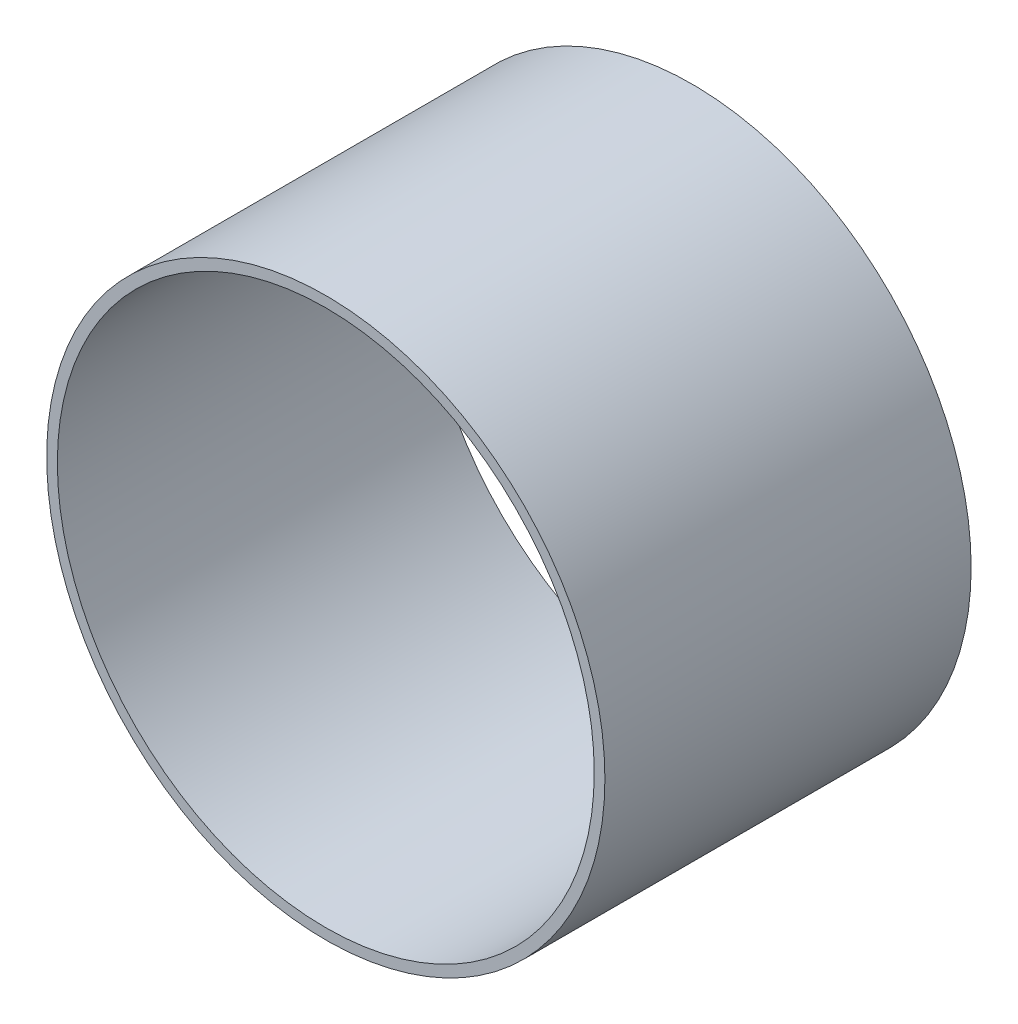
SolidWorks part; units mm, degrees
ref_plane "Спереди" through (0, 0, 0) normal (0, 0, 1) x (1, 0, 0)
ref_plane "Сверху" through (0, 0, 0) normal (0, 1, 0) x (1, 0, 0)
ref_plane "Справа" through (0, 0, 0) normal (1, 0, 0) x (0, 0, -1)
sketch "Эскиз1" plane through (0, 0, 0) normal (0, 0, 1) x (1, 0, 0)
  circle A0 centre (0, 0) radius 78.5
  circle A1 centre (0, 0) radius 75.5
extrude "Rim_reference" add sketch "Эскиз1" along normal blind 103 from offset 44.5
